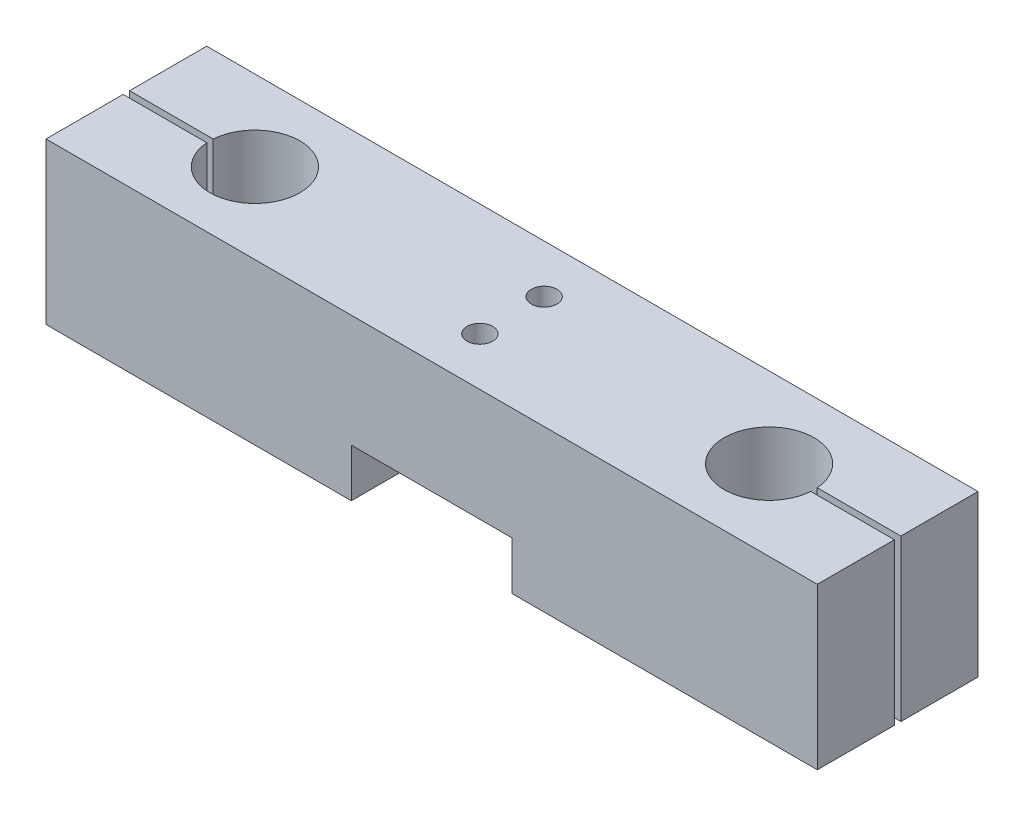
SolidWorks part; units mm, degrees
material "Дуб"
ref_plane "Спереди" through (0, 0, 0) normal (0, 0, 1) x (1, 0, 0)
ref_plane "Сверху" through (0, 0, 0) normal (0, 1, 0) x (1, 0, 0)
ref_plane "Справа" through (0, 0, 0) normal (1, 0, 0) x (0, 0, -1)
sketch "Эскиз1" plane through (0, 0, 0) normal (0, 1, 0) x (1, 0, 0)
  line L0 (0, 25) -> (200, 25) construction
  line L1 (0, 0) -> (240, 0)
  line L2 (0, 0) -> (0, 24)
  line L3 (0, 50) -> (240, 50)
  line L4 (240, 0) -> (240, 24)
  line L5 (0, 26) -> (26.0358, 26)
  line L6 (0, 24) -> (26.0358, 24)
  line L7 (240, 26) -> (213.9642, 26)
  line L8 (240, 24) -> (213.9642, 24)
  line L9 (240, 26) -> (240, 50)
  line L10 (0, 26) -> (0, 50)
  arc A0 (26.0358, 24) -> (26.0358, 26) centre (40, 25) ccw
  arc A1 (213.9642, 26) -> (213.9642, 24) centre (200, 25) ccw
  dimension "D3" = 28
  dimension "D4" = 28
  dimension "D1" = 50
  dimension "D2" = 240
  dimension "D5" = 40
  dimension "D6" = 40
  dimension "D7" = 1
  dimension "D8" = 1
extrude "Бобышка-Вытянуть1" add sketch "Эскиз1" along normal blind 50
sketch "Эскиз3" plane through (0, 0, 0) normal (0, -1, 0) x (1, 0, 0)
  line L0 (120, 0) -> (120, -50) construction
  line L1 (0, 0) -> (240, 0) construction
  line L2 (240, -50) -> (0, -50) construction
  line L4 (95, 0) -> (145, 0)
  line L5 (95, 0) -> (95, -50)
  line L6 (95, -50) -> (145, -50)
  line L7 (145, 0) -> (145, -50)
  dimension "D1" = 25
  dimension "D2" = 50
extrude "Вырез-Вытянуть1" cut sketch "Эскиз3" against normal blind 15
sketch "Эскиз4" plane through (0, 50, 0) normal (0, 1, 0) x (1, 0, 0)
  line L0 (120, 50) -> (120, 0) construction
  line L1 (240, 50) -> (0, 50) construction
  line L2 (0, 0) -> (240, 0) construction
  circle A0 centre (120, 35) radius 4
  circle A1 centre (120, 15) radius 4
  dimension "D1" = 8
  dimension "D2" = 8
  dimension "D4" = 15
  dimension "D3" = 15
extrude "Вырез-Вытянуть2" cut sketch "Эскиз4" against normal blind 50
